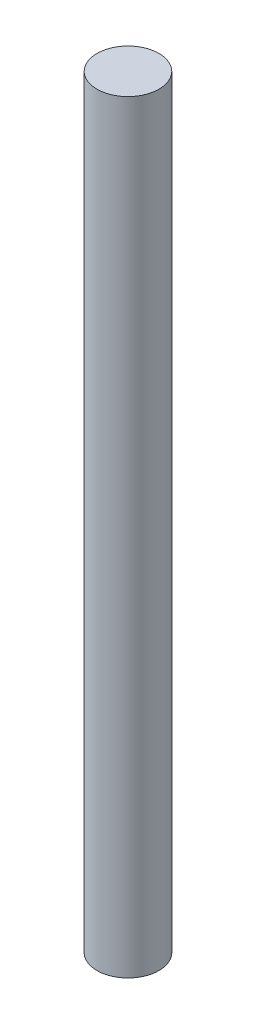
SolidWorks part; units mm, degrees
ref_plane "Front Plane" through (0, 0, 0) normal (0, 0, 1) x (1, 0, 0)
ref_plane "Top Plane" through (0, 0, 0) normal (0, 1, 0) x (1, 0, 0)
ref_plane "Right Plane" through (0, 0, 0) normal (1, 0, 0) x (0, 0, -1)
sketch "Sketch1" plane through (0, 0, 0) normal (0, 1, 0) x (1, 0, 0)
  circle A0 centre (0, 0) radius 1.59
extrude "Boss-Extrude1" add sketch "Sketch1" along normal blind 39.16
